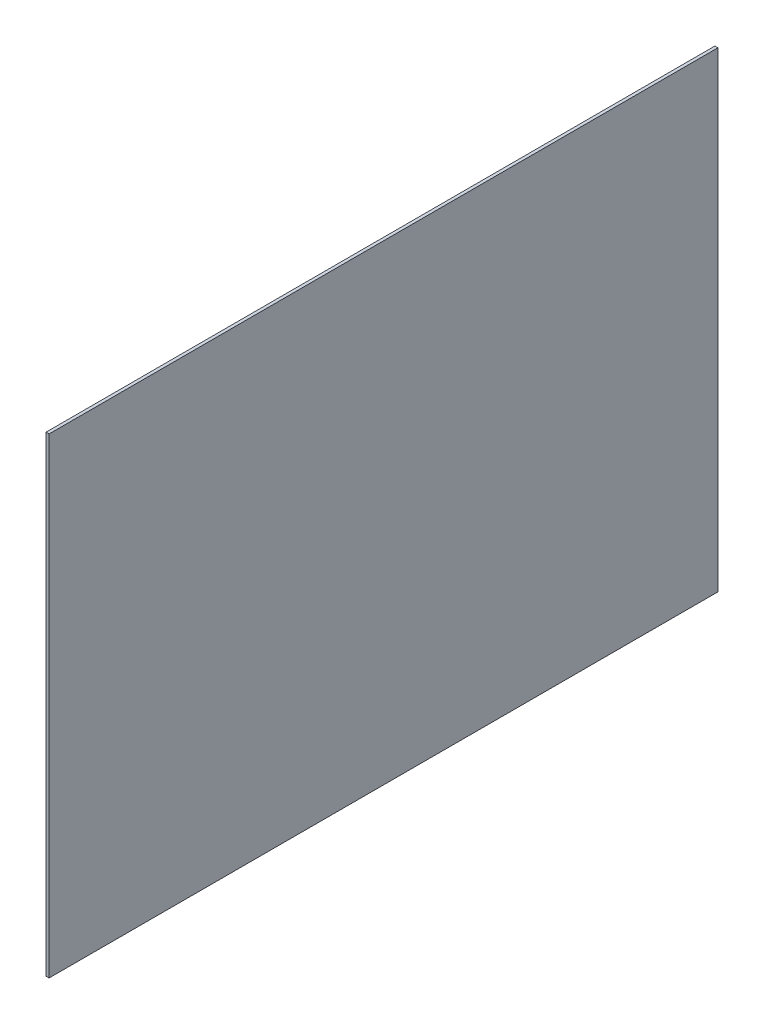
SolidWorks part; units mm, degrees
ref_plane "Plan de face" through (0, 0, 0) normal (0, 0, 1) x (1, 0, 0)
ref_plane "Plan de dessus" through (0, 0, 0) normal (0, 1, 0) x (1, 0, 0)
ref_plane "Plan de droite" through (0, 0, 0) normal (1, 0, 0) x (0, 0, -1)
sketch "Esquisse1" plane through (0, 0, 0) normal (1, 0, 0) x (0, 0, -1)
  line L0 (-247.9021, 0) -> (298.0882, 0) construction
  line L1 (0, 231.4618) -> (0, -251.3632) construction
  line L2 (-220, 155) -> (-220, -155)
  line L3 (-220, -155) -> (220, -155)
  line L4 (220, -155) -> (220, 155)
  line L5 (220, 155) -> (-220, 155)
  dimension "D1" = 440
  dimension "D2" = 310
extrude "Boss.-Extru.1" add sketch "Esquisse1" along normal blind 2 contours L5 L2 L3 L4
